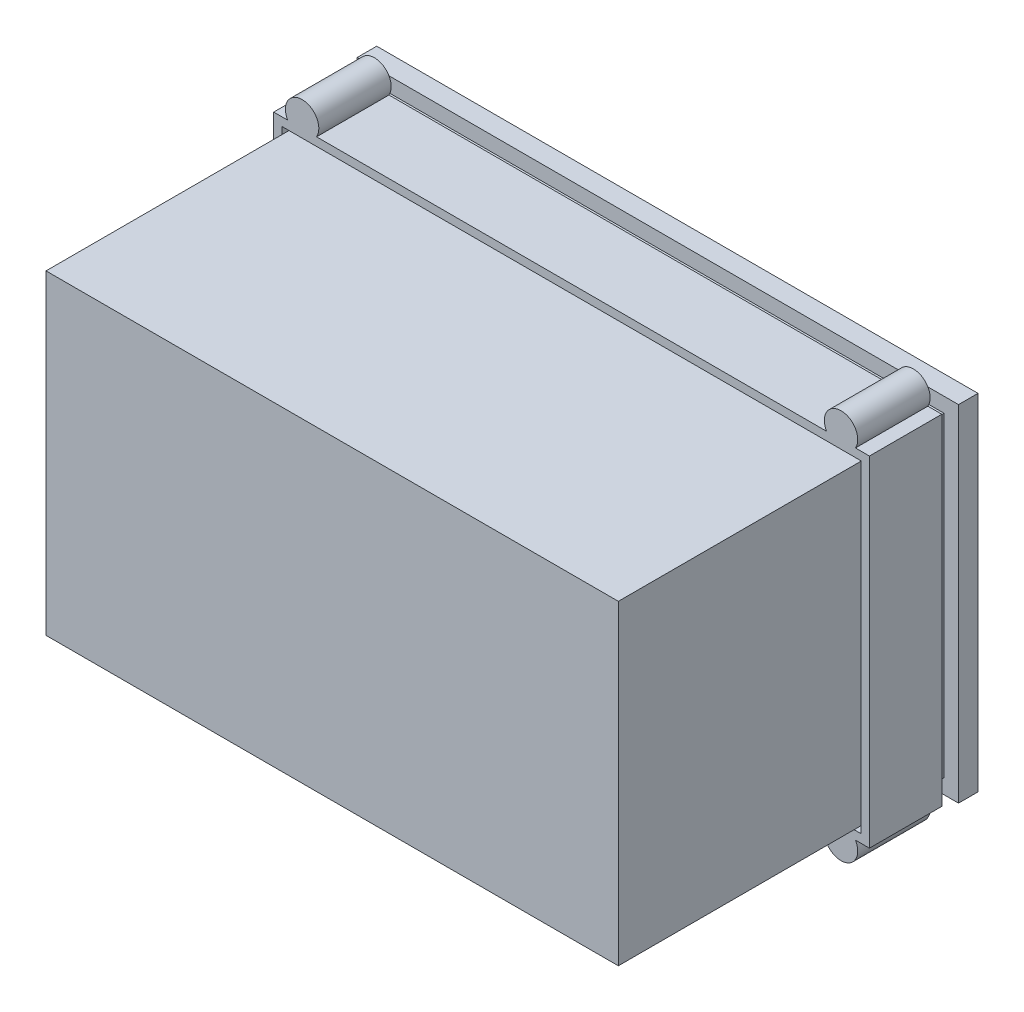
SolidWorks part; units mm, degrees
ref_plane "前视基准面" through (0, 0, 0) normal (0, 0, 1) x (1, 0, 0)
ref_plane "上视基准面" through (0, 0, 0) normal (0, 1, 0) x (1, 0, 0)
ref_plane "右视基准面" through (0, 0, 0) normal (1, 0, 0) x (0, 0, -1)
sketch "草图1" plane through (0, 0, 0) normal (0, 0, 1) x (1, 0, 0)
  line L1 (-54, -31) -> (54, -31)
  line L2 (-54, -31) -> (-54, 31)
  line L3 (-54, 31) -> (54, 31)
  line L4 (54, -31) -> (54, 31)
  line L5 (-54, -31) -> (54, 31) construction
  line L6 (-54, 31) -> (54, -31) construction
  point P0 (0, 0)
  dimension "D1" = 108
  dimension "D2" = 62
extrude "凸台-拉伸1" add sketch "草图1" along normal blind 62
sketch "草图2" plane through (0, 0, 62) normal (0, 0, 1) x (1, 0, 0)
  line L1 (51.4, -28.35) -> (-51.4, -28.35)
  line L2 (51.4, -28.35) -> (51.4, 28.35)
  line L3 (51.4, 28.35) -> (-51.4, 28.35)
  line L4 (-51.4, -28.35) -> (-51.4, 28.35)
  line L5 (51.4, -28.35) -> (-51.4, 28.35) construction
  line L6 (51.4, 28.35) -> (-51.4, -28.35) construction
  point P0 (0, 0)
  dimension "D1" = 102.8
  dimension "D2" = 56.7
extrude "切除-拉伸1" cut sketch "草图2" against normal blind 58.5 flip side to cut
sketch "草图3" plane through (0, 0, 0) normal (0, 0, -1) x (-1, 0, 0)
  line L0 (54, -31) -> (-54, -31) construction
  line L1 (-44, 1) -> (35, 1)
  line L2 (-44, 1) -> (-44, -21)
  line L3 (-44, -21) -> (35, -21)
  line L4 (35, 1) -> (35, -21)
  line L5 (-54, -31) -> (-54, 31) construction
  dimension "D1" = 79
  dimension "D2" = 22
  dimension "D3" = 10
  dimension "D4" = 10
extrude "切除-拉伸2" cut sketch "草图3" against normal blind 1
sketch "草图4" plane through (0, 0, 1) normal (0, 0, -1) x (-1, 0, 0)
  line L1 (-36, -8) -> (26, -8)
  line L2 (-36, -8) -> (-36, -13)
  line L3 (-36, -13) -> (26, -13)
  line L4 (26, -8) -> (26, -13)
  line L5 (-44, -21) -> (35, -21) construction
  line L6 (-44, 1) -> (-44, -21) construction
  dimension "D1" = 62
  dimension "D2" = 5
  dimension "D3" = 8
  dimension "D4" = 8
extrude "切除-拉伸3" cut sketch "草图4" against normal blind 30
sketch "草图5" plane through (0, 0, 0) normal (0, 0, -1) x (-1, 0, 0)
  line L0 (51, 28) -> (-51, 28)
  line L1 (50, -27) -> (43, -27)
  line L2 (50, -27) -> (50, 27)
  line L3 (50, 27) -> (43, 27)
  line L4 (-50, -27) -> (-50, 27)
  line L5 (50, -27) -> (-50, 27) construction
  line L6 (50, 27) -> (-50, -27) construction
  line L7 (-51, -28) -> (-51, 28)
  line L8 (51, -28) -> (-51, -28)
  line L9 (51, -28) -> (51, 28)
  line L10 (43, -27) -> (43, 27)
  line L11 (42, -27) -> (42, 27)
  line L12 (42, 27) -> (-50, 27)
  line L13 (42, -27) -> (-50, -27)
  line L14 (50, 27) -> (-50, 27) construction
  line L16 (50, -27) -> (-50, -27) construction
  point P0 (0, 0)
  dimension "D1" = 100
  dimension "D2" = 54
  dimension "D3" = 1
  dimension "D4" = 7
  dimension "D5" = 1
extrude "切除-拉伸4" cut sketch "草图5" against normal blind 2
sketch "草图6" plane through (0, 0, 0) normal (0, 0, -1) x (-1, 0, 0)
  line L0 (46.5, -15.9909) -> (46.5, -21.9909) construction
  line L1 (48, -15.9909) -> (48, -21.9909)
  line L2 (45, -15.9909) -> (45, -21.9909)
  line L3 (50, -27) -> (50, 27) construction
  circle A0 centre (46.5, 20.426) radius 1.5
  circle A1 centre (46.5, 8.8064) radius 1.5
  circle A2 centre (46.5, -5.3448) radius 1.5
  arc A3 (48, -15.9909) -> (45, -15.9909) centre (46.5, -15.9909) ccw
  arc A4 (45, -21.9909) -> (48, -21.9909) centre (46.5, -21.9909) ccw
  point P8 (46.5, -18.9909)
  dimension "D4" = 3
  dimension "D5" = 3
  dimension "D6" = 3
  dimension "D1" = 3
  dimension "D2" = 6
  dimension "D3" = 3.5
extrude "凸台-拉伸2" add sketch "草图6" along normal blind 3
sketch "草图7" plane through (0, 0, 62) normal (0, 0, 1) x (1, 0, 0)
  line L0 (-50.9981, -30.5) -> (-53.5, -30.5)
  line L1 (45.8019, -30.5) -> (-45.8019, -30.5)
  line L2 (-50.9981, 30.5) -> (-53.5, 30.5)
  line L3 (-51.4, 28.35) -> (-51.4, -28.35) construction
  line L4 (51.4, -28.35) -> (51.4, 28.35) construction
  line L5 (45.8019, 30.5) -> (-45.8019, 30.5)
  line L6 (52, -29) -> (-52, -29)
  line L7 (52, -29) -> (52, 29)
  line L8 (52, 29) -> (-52, 29)
  line L9 (-52, -29) -> (-52, 29)
  line L10 (52, -29) -> (-52, 29) construction
  line L11 (52, 29) -> (-52, -29) construction
  line L12 (53.5, -30.5) -> (50.9981, -30.5)
  line L14 (53.5, -30.5) -> (53.5, 30.5)
  line L15 (53.5, 30.5) -> (50.9981, 30.5)
  line L18 (-53.5, -30.5) -> (-53.5, 30.5)
  line L19 (53.5, -30.5) -> (-53.5, 30.5) construction
  line L20 (53.5, 30.5) -> (-53.5, -30.5) construction
  arc A0 (-45.8019, 30.5) -> (-50.9981, 30.5) centre (-48.4, 32) ccw
  arc A1 (50.9981, 30.5) -> (45.8019, 30.5) centre (48.4, 32) ccw
  arc A2 (-50.9981, -30.5) -> (-45.8019, -30.5) centre (-48.4, -32) ccw
  arc A3 (45.8019, -30.5) -> (50.9981, -30.5) centre (48.4, -32) ccw
  point P12 (0, 0)
  point P18 (0, 0)
  point P24 (0, 0)
  dimension "D1" = 6
  dimension "D2" = 6
  dimension "D3" = 6
  dimension "D4" = 6
  dimension "D6" = 104
  dimension "D7" = 58
  dimension "D8" = 61
  dimension "D9" = 107
extrude "凸台-拉伸4" add sketch "草图7" against normal blind 56 separate body
sketch "草图8" plane through (0, 0, 62) normal (0, 0, 1) x (1, 0, 0)
  line L1 (51.4, -28.35) -> (-51.4, -28.35)
  line L2 (51.4, -28.35) -> (51.4, 28.35)
  line L3 (51.4, 28.35) -> (-51.4, 28.35)
  line L4 (-51.4, -28.35) -> (-51.4, 28.35)
  line L5 (51.4, -28.35) -> (-51.4, 28.35) construction
  line L6 (51.4, 28.35) -> (-51.4, -28.35) construction
  point P0 (0, 0)
extrude "切除-拉伸5" cut sketch "草图8" against normal blind 43 flip side to cut
